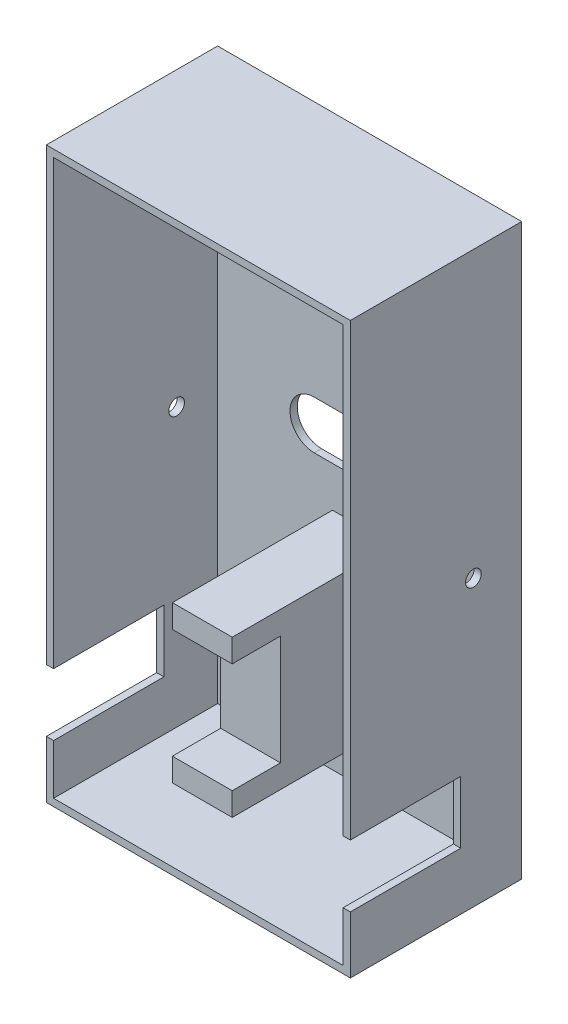
SolidWorks part; units mm, degrees
ref_plane "Front Plane" through (0, 0, 0) normal (0, 0, 1) x (1, 0, 0)
ref_plane "Top Plane" through (0, 0, 0) normal (0, 1, 0) x (1, 0, 0)
ref_plane "Right Plane" through (0, 0, 0) normal (1, 0, 0) x (0, 0, -1)
ref_plane "Plane1" through (0, 0, 34) normal (0, 0, 1) x (1, 0, 0)
sketch "Sketch1" plane through (0, 0, 34) normal (0, 0, 1) x (1, 0, 0)
  line L0 (-1.5, -1.5) -> (61.5, -1.5)
  line L1 (61.5, -1.5) -> (61.5, 116.5)
  line L2 (61.5, 116.5) -> (-1.5, 116.5)
  line L3 (-1.5, 116.5) -> (-1.5, -1.5)
extrude "Boss-Extrude1" add sketch "Sketch1" against normal blind 35.5
sketch "Sketch2" plane through (0, 0, 34) normal (0, 0, 1) x (1, 0, 0)
  line L0 (0, 115) -> (0, 0)
  line L1 (0, 0) -> (60, 0)
  line L2 (60, 0) -> (60, 115)
  line L3 (60, 115) -> (0, 115)
extrude "Cut-Extrude1" cut sketch "Sketch2" against normal blind 34
sketch "Sketch3" plane through (0, 0, 0) normal (0, 0, 1) x (1, 0, 0)
  line L0 (36.2, 43.3) -> (36.2, 17.55)
  line L1 (36.2, 17.55) -> (23.8, 17.55)
  line L2 (23.8, 17.55) -> (23.8, 43.3)
  line L3 (23.8, 43.3) -> (36.2, 43.3)
  line L4 (23.8, 30.425) -> (0, 30.425) construction
  line L5 (0, 115) -> (0, 0) construction
  line L6 (36.2, 30.425) -> (60, 30.425) construction
  line L7 (60, 0) -> (60, 115) construction
  line L8 (0, 0) -> (60, 0) construction
  line L9 (30, 17.55) -> (30, 19.05) construction
  line L10 (23.8, 14.25) -> (36.2, 14.25)
  line L11 (23.8, 14.25) -> (23.8, 19.05)
  line L12 (23.8, 19.05) -> (36.2, 19.05)
  line L13 (36.2, 14.25) -> (36.2, 19.05)
  line L14 (23.8, 14.25) -> (36.2, 19.05) construction
  line L15 (23.8, 19.05) -> (36.2, 14.25) construction
  line L16 (23.8, 41.8) -> (36.2, 41.8)
  line L17 (23.8, 41.8) -> (23.8, 46.6)
  line L18 (23.8, 46.6) -> (36.2, 46.6)
  line L19 (36.2, 41.8) -> (36.2, 46.6)
  line L20 (23.8, 41.8) -> (36.2, 46.6) construction
  line L21 (23.8, 46.6) -> (36.2, 41.8) construction
  line L22 (30, 41.8) -> (30, 43.3) construction
  point P14 (30, 16.65)
  point P19 (30, 44.2)
  point P20 (30, 17.55)
  point P26 (30, 43.3)
  dimension "D1" = 25.75
  dimension "D2" = 12.4
  dimension "D3" = 17.55
  dimension "D4" = 1.5
  dimension "D5" = 4.8
extrude "Boss-Extrude2" add sketch "Sketch3" along normal blind 33.18 contours L10 L13 L1 L11 | L12 L2 L1 L0 | L16 L2 L12 L0 | L3 L19 L18 L17 | L2 L16 L0 L3
sketch "Sketch4" plane through (23.8, 0, 0) normal (-1, 0, 0) x (0, 0, 1)
  line L0 (33.18, 19.05) -> (33.18, 41.8)
  line L1 (33.18, 41.8) -> (23.18, 41.8)
  line L2 (23.18, 41.8) -> (23.18, 19.05)
  line L3 (23.18, 19.05) -> (33.18, 19.05)
  line L5 (33.18, 46.6) -> (0, 46.6) construction
  line L6 (33.18, 14.25) -> (33.18, 46.6) construction
  dimension "D1" = 22.75
  dimension "D2" = 4.8
  dimension "D3" = 10
extrude "Cut-Extrude2" cut sketch "Sketch4" against normal up to next
sketch "Sketch5" plane through (61.5, 0, 0) normal (1, 0, 0) x (0, 0, -1)
  line L0 (-34, 23.25) -> (-34, 10.36)
  line L1 (-34, 10.36) -> (-11.13, 10.36)
  line L2 (-11.13, 10.36) -> (-11.13, 23.25)
  line L3 (-11.13, 23.25) -> (-34, 23.25)
extrude "Cut-Extrude3" cut sketch "Sketch5" against normal up to next
sketch "Sketch6" plane through (-1.5, 0, 0) normal (-1, 0, 0) x (0, 0, 1)
  line L0 (34, 10.36) -> (34, 23.25)
  line L1 (34, 23.25) -> (11.13, 23.25)
  line L2 (11.13, 23.25) -> (11.13, 10.36)
  line L3 (11.13, 10.36) -> (34, 10.36)
extrude "Cut-Extrude4" cut sketch "Sketch6" against normal up to next
sketch "Sketch7" plane through (0, 0, -1.5) normal (0, 0, -1) x (-1, 0, 0)
  line L0 (-40, 55) -> (-20, 55)
  line L1 (-20, 65) -> (-40, 65)
  arc A0 (-20, 55) -> (-20, 65) centre (-20, 60) ccw
  arc A1 (-40, 65) -> (-40, 55) centre (-40, 60) ccw
extrude "Cut-Extrude5" cut sketch "Sketch7" against normal through all
hole_wizard "M2.5 Clearance Hole1" positions "Sketch9" profile "Sketch8" hole size "M2.5" standard "ANSI Metric"
sketch "Sketch9" plane through (0, 0, -1.5) normal (0, 0, -1) x (-1, 0, 0)
  point P0 (-9.95, 28.42)
  point P1 (-9.95, 21.935)
  point P2 (-50.05, 28.42)
  point P3 (-50.05, 21.935)
sketch "Sketch8" plane through (9.95, 28.42, -1.5) normal (1, 0, 0) x (0, 1, 0)
  line L0 (0, 0) -> (0, 35.5)
  line L1 (0, 35.5) -> (1.525, 35.5)
  line L2 (1.525, 35.5) -> (1.525, 0)
  line L5 (1.525, 0) -> (0, 0)
  line L11 (0, -6.35) -> (0, 107.95) construction
  dimension "Thru Hole Dia." = 3.05
  dimension "Thru Hole Depth" = 35.5
hole_wizard "M3 Clearance Hole1" positions "Sketch11" profile "Sketch10" hole size "M3" standard "ANSI Metric"
sketch "Sketch11" plane through (0, 0, 0) normal (1, 0, 0) x (0, 0, -1)
  point P0 (-8.5, 57.5)
sketch "Sketch10" plane through (0, 57.5, 8.5) normal (0, 1, 0) x (0, 0, -1)
  line L0 (0, 0) -> (0, 1.5)
  line L1 (0, 1.5) -> (1.6256, 1.5)
  line L2 (1.6256, 1.5) -> (1.6256, 0)
  line L5 (1.6256, 0) -> (0, 0)
  line L11 (0, -6.35) -> (0, 107.95) construction
  dimension "Thru Hole Dia." = 3.2512
  dimension "Thru Hole Depth" = 1.5
hole_wizard "M3 Clearance Hole2" positions "Sketch13" profile "Sketch12" hole size "M3" standard "ANSI Metric"
sketch "Sketch13" plane through (61.5, 0, 0) normal (1, 0, 0) x (0, 0, -1)
  point P0 (-8.5, 57.5)
sketch "Sketch12" plane through (61.5, 57.5, 8.5) normal (0, 1, 0) x (0, 0, -1)
  line L0 (0, 0) -> (0, 63)
  line L1 (0, 63) -> (1.6256, 63)
  line L2 (1.6256, 63) -> (1.6256, 0)
  line L5 (1.6256, 0) -> (0, 0)
  line L11 (0, -6.35) -> (0, 107.95) construction
  dimension "Thru Hole Dia." = 3.2512
  dimension "Thru Hole Depth" = 63
ref_plane "Plane2" through (0, 0, 34) normal (0, 0, 1) x (1, 0, 0)
equation "\"D1@Sketch3\"=1.5*2+22.5+.25"
equation "\"D1@Boss-Extrude2\"=17.48mm+15.7"
